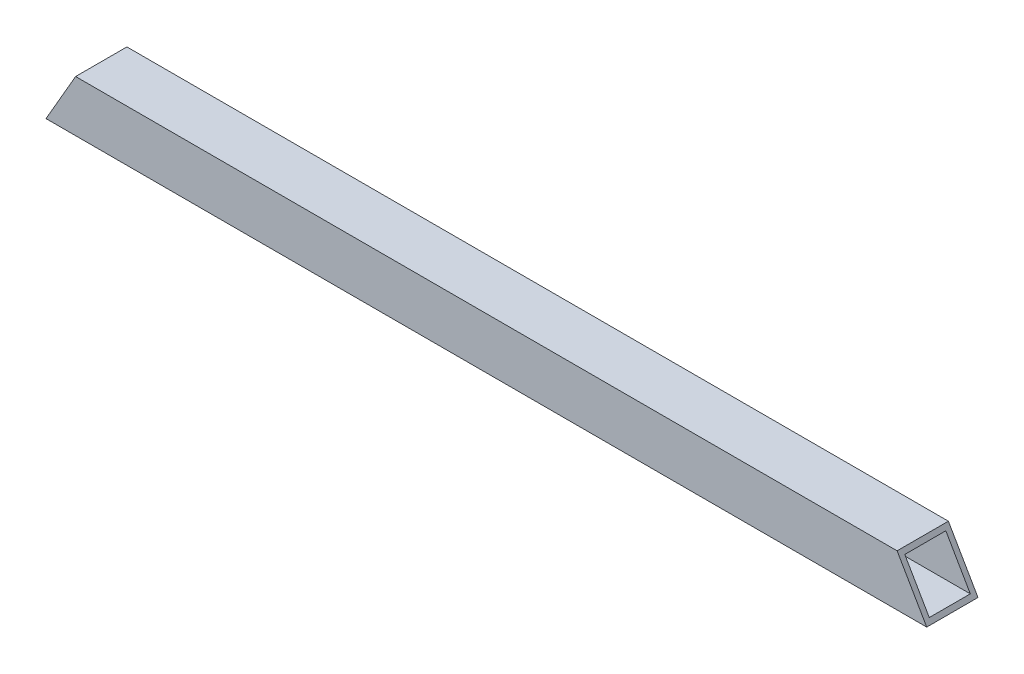
SolidWorks part; units mm, degrees
ref_plane "Front Plane" through (0, 0, 0) normal (0, 0, 1) x (1, 0, 0)
ref_plane "Top Plane" through (0, 0, 0) normal (0, 1, 0) x (1, 0, 0)
ref_plane "Right Plane" through (0, 0, 0) normal (1, 0, 0) x (0, 0, -1)
sketch "Sketch1" plane through (0, 0, 0) normal (0, 0, 1) x (1, 0, 0)
  line L0 (-48.4211, 24.6053) -> (271.9889, 24.6053)
  line L1 (-59.9711, 4.6053) -> (283.5389, 4.6053)
  line L2 (271.9889, 24.6053) -> (283.5389, 4.6053)
  line L3 (-48.4211, 24.6053) -> (-59.9711, 4.6053)
  point P4 (111.7839, 24.6053)
  point P5 (111.7839, 4.6053)
  dimension "D1" = 20
  dimension "D2" = 320.41
  dimension "D3" = 343.51
extrude "Boss-Extrude1" add sketch "Sketch1" along normal blind 20
sketch "Sketch2" plane through (214.621, 123.9436, 0) normal (0.866, 0.5001, 0) x (0, 0, -1)
  line L0 (0, -137.809) -> (0, -114.7135) construction
  line L1 (-18, -116.7135) -> (-2, -116.7135)
  line L2 (-18, -116.7135) -> (-18, -135.809)
  line L3 (-18, -135.809) -> (-2, -135.809)
  line L4 (-2, -116.7135) -> (-2, -135.809)
  line L5 (-18, -116.7135) -> (-2, -135.809) construction
  line L6 (-18, -135.809) -> (-2, -116.7135) construction
  line L7 (-20, -137.809) -> (-20, -114.7135) construction
  line L8 (-20, -137.809) -> (0, -137.809) construction
  line L9 (-20, -114.7135) -> (0, -114.7135) construction
  point P0 (-10, -126.2613)
  dimension "D1" = 2
  dimension "D2" = 2
  dimension "D3" = 2
  dimension "D4" = 2
sketch "Sketch3" plane through (0, 0, 0) normal (1, 0, 0) x (0, 0, -1)
  line L4 (-2, 22.8733) -> (-18, 22.8733)
  line L5 (-2, 6.3372) -> (-2, 22.8733)
  line L6 (-18, 6.3372) -> (-2, 6.3372)
  line L7 (-18, 22.8733) -> (-18, 6.3372)
  line L8 (-2, 22.8733) -> (-18, 22.8733)
  line L9 (-2, 6.3372) -> (-2, 22.8733)
  line L10 (-18, 6.3372) -> (-2, 6.3372)
  line L11 (-18, 22.8733) -> (-18, 6.3372)
  dimension "D1" = 0
extrude "Cut-Extrude1" cut sketch "Sketch3" against normal through all both and the other way through all
